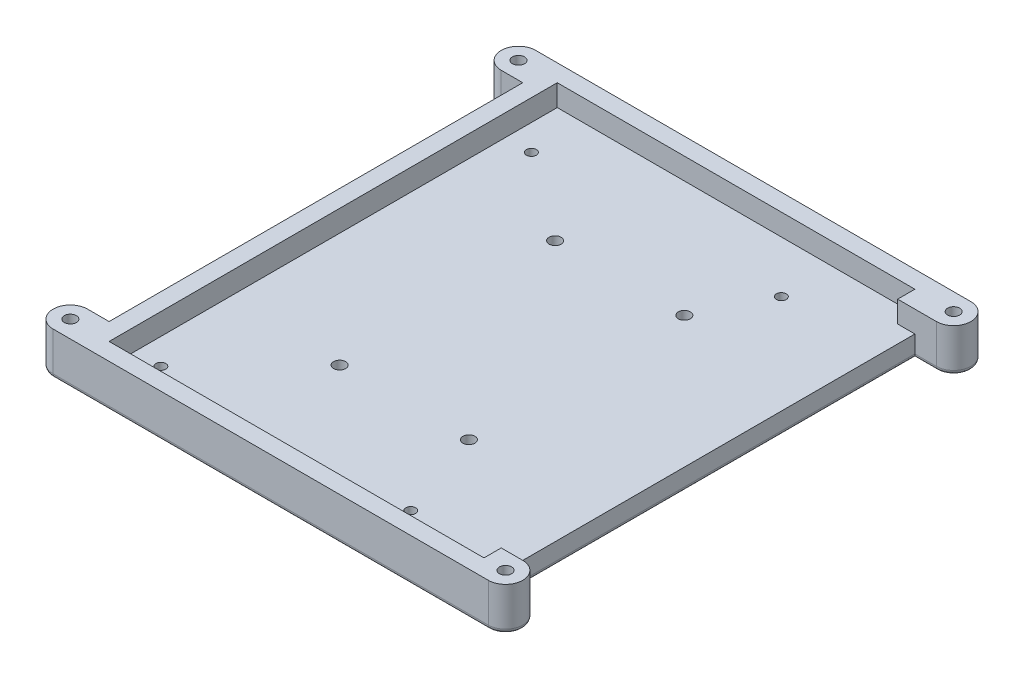
SolidWorks part; units mm, degrees
ref_plane "Front Plane" through (0, 0, 0) normal (0, 0, 1) x (1, 0, 0)
ref_plane "Top Plane" through (0, 0, 0) normal (0, 1, 0) x (1, 0, 0)
ref_plane "Right Plane" through (0, 0, 0) normal (1, 0, 0) x (0, 0, -1)
sketch "Sketch1" plane through (0, 0, 0) normal (0, 1, 0) x (1, 0, 0)
  line L0 (0, 56) -> (0, -56) construction
  line L1 (-39.5, 50) -> (39.5, 50) construction
  line L2 (-39.5, 50) -> (-39.5, -50) construction
  line L3 (-39.5, -50) -> (39.5, -50) construction
  line L4 (39.5, 50) -> (39.5, -50) construction
  line L5 (-45.5, 56) -> (45.5, 56)
  line L6 (-45.5, 56) -> (-45.5, -56)
  line L7 (-45.5, -56) -> (45.5, -56)
  line L8 (45.5, 56) -> (45.5, -56)
  circle A0 centre (-35.5, -46) radius 1.15
  circle A1 centre (22.5, -46) radius 1.15
  circle A2 centre (22.5, 40) radius 1.15
  circle A3 centre (-35.5, 40) radius 1.15
  point P4 (-39.5, 0)
  point P6 (0, 50)
  dimension "D5" = 2.3
  dimension "D6" = 86
  dimension "D7" = 58
  dimension "D8" = 4
  dimension "D9" = 4
  dimension "D1" = 79
  dimension "D2" = 100
  dimension "D3" = 112
  dimension "D4" = 91
extrude "Base" add sketch "Sketch1" along normal blind 10
sketch "Sketch2" plane through (0, 10, 0) normal (0, 1, 0) x (1, 0, 0)
  line L0 (0, 52) -> (0, -52) construction
  line L1 (-41.5, 52) -> (41.5, 52)
  line L2 (-41.5, 52) -> (-41.5, -52)
  line L3 (-41.5, -52) -> (41.5, -52)
  line L4 (41.5, 52) -> (41.5, -52)
  line L5 (-45.5, -56) -> (45.5, -56) construction
  line L6 (-45.5, 56) -> (-45.5, -56) construction
  dimension "D1" = 4
  dimension "D2" = 4
extrude "Module Cutout" cut sketch "Sketch2" against normal blind 5
sketch "Sketch3" plane through (0, 10, 0) normal (0, 1, 0) x (1, 0, 0)
  line L0 (-45.5, 56) -> (-50.5, 56)
  line L1 (-45.5, 56) -> (-45.5, -56) construction
  line L2 (-45.5, 56) -> (-45.5, 48)
  line L3 (-45.5, 48) -> (-50.5, 48)
  line L4 (45.5, 56) -> (-45.5, 56) construction
  line L5 (0, 56) -> (0, -56) construction
  line L6 (-45.5, -56) -> (45.5, -56) construction
  line L7 (45.5, 48) -> (50.5, 48)
  line L8 (45.5, 56) -> (45.5, 48)
  line L9 (45.5, 56) -> (50.5, 56)
  line L10 (-45.5, 0) -> (45.5, 0) construction
  line L11 (45.5, -56) -> (45.5, 56) construction
  line L12 (45.5, -56) -> (50.5, -56)
  line L13 (45.5, -56) -> (45.5, -48)
  line L14 (45.5, -48) -> (50.5, -48)
  line L15 (-45.5, -48) -> (-50.5, -48)
  line L16 (-45.5, -56) -> (-45.5, -48)
  line L17 (-45.5, -56) -> (-50.5, -56)
  arc A0 (-50.5, 48) -> (-50.5, 56) centre (-50.5, 52) cw
  circle A1 centre (-50.5, 52) radius 1.4
  circle A2 centre (50.5, 52) radius 1.4
  arc A3 (50.5, 48) -> (50.5, 56) centre (50.5, 52) ccw
  arc A4 (50.5, -48) -> (50.5, -56) centre (50.5, -52) cw
  circle A5 centre (50.5, -52) radius 1.4
  circle A6 centre (-50.5, -52) radius 1.4
  arc A7 (-50.5, -48) -> (-50.5, -56) centre (-50.5, -52) ccw
  dimension "D1" = 2.8
  dimension "D2" = 8
  dimension "D3" = 5
extrude "Case Assembly Holes" add sketch "Sketch3" against normal up to surface (10 mm away) up to face at (0, 0, 0)
sketch "Sketch5" plane through (0, 10, 0) normal (0, 1, 0) x (1, 0, 0)
  line L0 (41.5, -52) -> (41.5, 52) construction
  line L1 (41.5, 48) -> (45.5, 48)
  line L2 (41.5, 48) -> (41.5, -52)
  line L3 (41.5, -52) -> (45.5, -52)
  line L4 (45.5, 48) -> (45.5, -52)
  line L5 (-41.5, -52) -> (41.5, -52) construction
  line L6 (45.5, -48) -> (45.5, 48) construction
  line L7 (45.5, 48) -> (50.5, 48) construction
extrude "Ports Side Recess" cut sketch "Sketch5" against normal up to surface (5 mm away) up to face at (-35.5, 5, 47.15)
sketch "Sketch4" plane through (0, 0, 0) normal (0, -1, 0) x (1, 0, 0)
  line L0 (0, 25) -> (0, -25) construction
  line L1 (-15, 25) -> (15, 25) construction
  line L2 (-15, 25) -> (-15, -25) construction
  line L3 (-15, -25) -> (15, -25) construction
  line L4 (15, 25) -> (15, -25) construction
  circle A0 centre (-15, 25) radius 1.4
  circle A1 centre (-15, -25) radius 1.4
  circle A2 centre (15, -25) radius 1.4
  circle A3 centre (15, 25) radius 1.4
  point P7 (-15, 0)
  dimension "D3" = 2.8
  dimension "D1" = 30
  dimension "D2" = 50
extrude "Basket Clamp Mounting Holes" cut sketch "Sketch4" against normal up to next
fillet "1mm Edge Fillets" radius 1 12 edges at (48, 0, 48) (-48, 0, 48) (-54.5, 0, 52) (0, 0, 56) (48, 0, -48) (54.5, 0, -52) (-48, 0, -48) (-54.5, 0, -52) (-45.5, 0, 0) (54.5, 0, 52) (45.5, 0, 0) (0, 0, -56)
